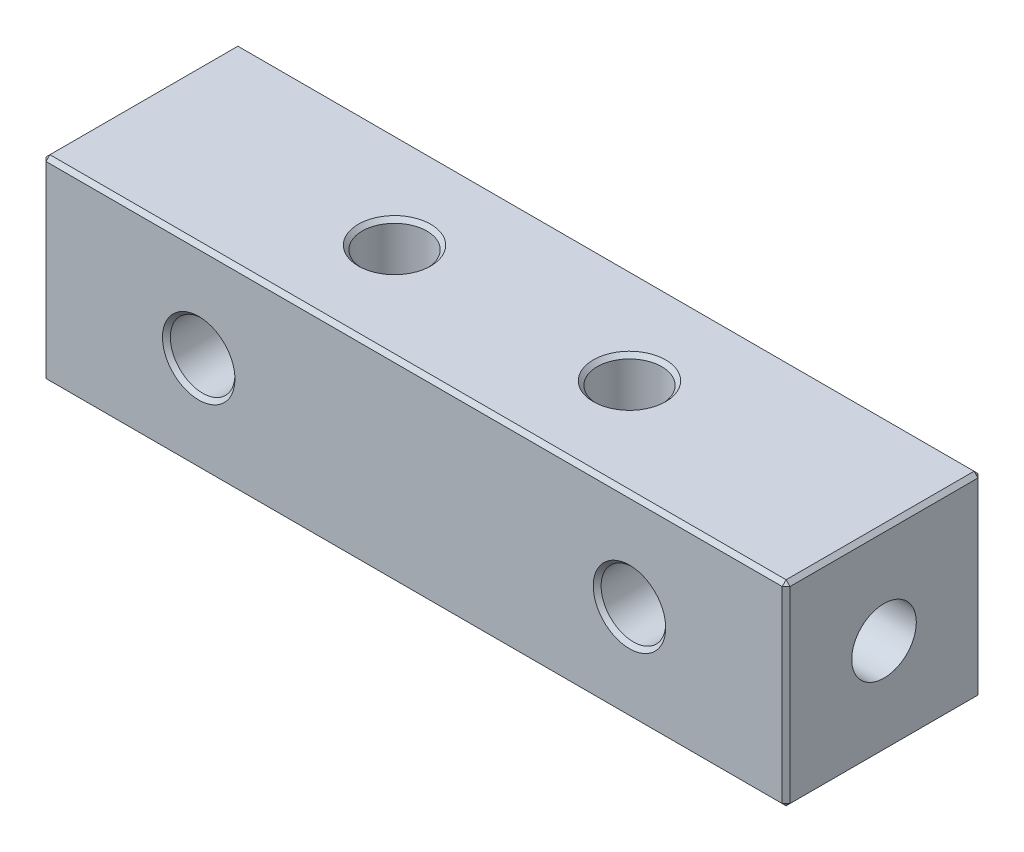
SolidWorks part; units mm, degrees
ref_plane "前视基准面" through (0, 0, 0) normal (0, 0, 1) x (1, 0, 0)
ref_plane "上视基准面" through (0, 0, 0) normal (0, 1, 0) x (1, 0, 0)
ref_plane "右视基准面" through (0, 0, 0) normal (1, 0, 0) x (0, 0, -1)
sketch "草图1" plane through (0, 0, 0) normal (0, 1, 0) x (1, 0, 0)
  line L1 (-19, 5) -> (19, 5)
  line L2 (-19, 5) -> (-19, -5)
  line L3 (-19, -5) -> (19, -5)
  line L4 (19, 5) -> (19, -5)
  line L5 (-19, 5) -> (19, -5) construction
  line L6 (-19, -5) -> (19, 5) construction
  point P0 (0, 0)
  dimension "D1" = 10
  dimension "D2" = 38
extrude "凸台-拉伸1" add sketch "草图1" along normal mid plane 10
hole_wizard "M4 螺纹孔1" positions "草图4" profile "草图6" tap size "M4" standard "GB" end condition through all
sketch "草图4" plane through (0, 5, 0) normal (0, 1, 0) x (1, 0, 0)
  line L0 (-19, 5) -> (-19, -5) construction
  line L1 (0, 0) -> (-50000, 0) construction
  point P0 (-6, 0)
  point P2 (6, 0)
  dimension "D1" = 13
  dimension "D2" = 12
sketch "草图6" plane through (-6, 5, 0) normal (1, 0, 0) x (0, 0, 1)
  line L0 (0, 0) -> (0, 10)
  line L1 (0, 10) -> (1.65, 10)
  line L2 (1.65, 10) -> (1.65, 0)
  line L5 (1.65, 0) -> (0, 0)
  line L11 (0, -6.35) -> (0, 107.95) construction
  dimension "通孔螺纹孔钻头直径" = 3.3
  dimension "通孔螺纹孔钻头深度" = 10
cosmetic thread "孔螺蚊线1" parameters "D2"=4
cosmetic thread "孔螺蚊线7" parameters "D2"=4
hole_wizard "M4 螺纹孔2" positions "草图7" profile "草图8" tap size "M4" standard "GB" end condition through all
sketch "草图7" plane through (0, 0, -5) normal (0, 0, -1) x (-1, 0, 0)
  line L0 (0, 0) -> (-50000, 0) construction
  line L1 (-19, 5) -> (-19, -5) construction
  point P0 (-11, 0)
  point P2 (11, 0)
  dimension "D1" = 8
  dimension "D2" = 22
sketch "草图8" plane through (11, 0, -5) normal (1, 0, 0) x (0, 1, 0)
  line L0 (0, 0) -> (0, 10)
  line L1 (0, 10) -> (1.65, 10)
  line L2 (1.65, 10) -> (1.65, 0)
  line L5 (1.65, 0) -> (0, 0)
  line L11 (0, -6.35) -> (0, 107.95) construction
  dimension "通孔螺纹孔钻头直径" = 3.3
  dimension "通孔螺纹孔钻头深度" = 10
cosmetic thread "孔螺蚊线3"
cosmetic thread "孔螺蚊线4"
chamfer "倒角1" distance 0.2 angle 45 20 edges at (6, -5, 1.65) (-6, -5, 1.65) (-12.65, 0, 5) (9.35, 0, 5) (6, 5, 1.65) (-6, 5, 1.65) (-19, -5, 0) (19, -5, 0) (-19, 0, 5) (0, -5, 5) (19, 0, 5) (0, 5, 5) (-19, 5, 0) (19, 5, 0) (19, 0, -5) (0, 5, -5) (-19, 0, -5) (0, -5, -5) (-12.65, 0, -5) (9.35, 0, -5)
hole_wizard "M4 螺纹孔3" positions "草图9" profile "草图10" tap size "M4" standard "GB"
sketch "草图9" plane through (-19, 0, 0) normal (-1, 0, 0) x (0, 0, 1)
  point P0 (0, 0)
sketch "草图10" plane through (-19, 0, 0) normal (0, 1, 0) x (0, 0, 1)
  line L0 (0, 0) -> (0, 6.35)
  line L1 (0, 6.35) -> (1.65, 6.35)
  line L2 (1.65, 6.35) -> (1.65, 0)
  line L5 (1.65, 0) -> (0, 0)
  line L11 (0, -6.35) -> (0, 107.95) construction
  dimension "通孔螺纹孔钻头直径" = 3.3
  dimension "通孔螺纹孔钻头深度" = 6.35
cosmetic thread "孔螺蚊线5" parameters "D2"=4
hole_wizard "M4 螺纹孔4" positions "草图11" profile "草图12" tap size "M4" standard "GB"
sketch "草图11" plane through (19, 0, 0) normal (1, 0, 0) x (0, 0, -1)
  point P0 (0, 0)
sketch "草图12" plane through (19, 0, 0) normal (0, 1, 0) x (0, 0, -1)
  line L0 (0, 0) -> (0, 6.35)
  line L1 (0, 6.35) -> (1.65, 6.35)
  line L2 (1.65, 6.35) -> (1.65, 0)
  line L5 (1.65, 0) -> (0, 0)
  line L11 (0, -6.35) -> (0, 107.95) construction
  dimension "通孔螺纹孔钻头直径" = 3.3
  dimension "通孔螺纹孔钻头深度" = 6.35
cosmetic thread "孔螺蚊线6"
